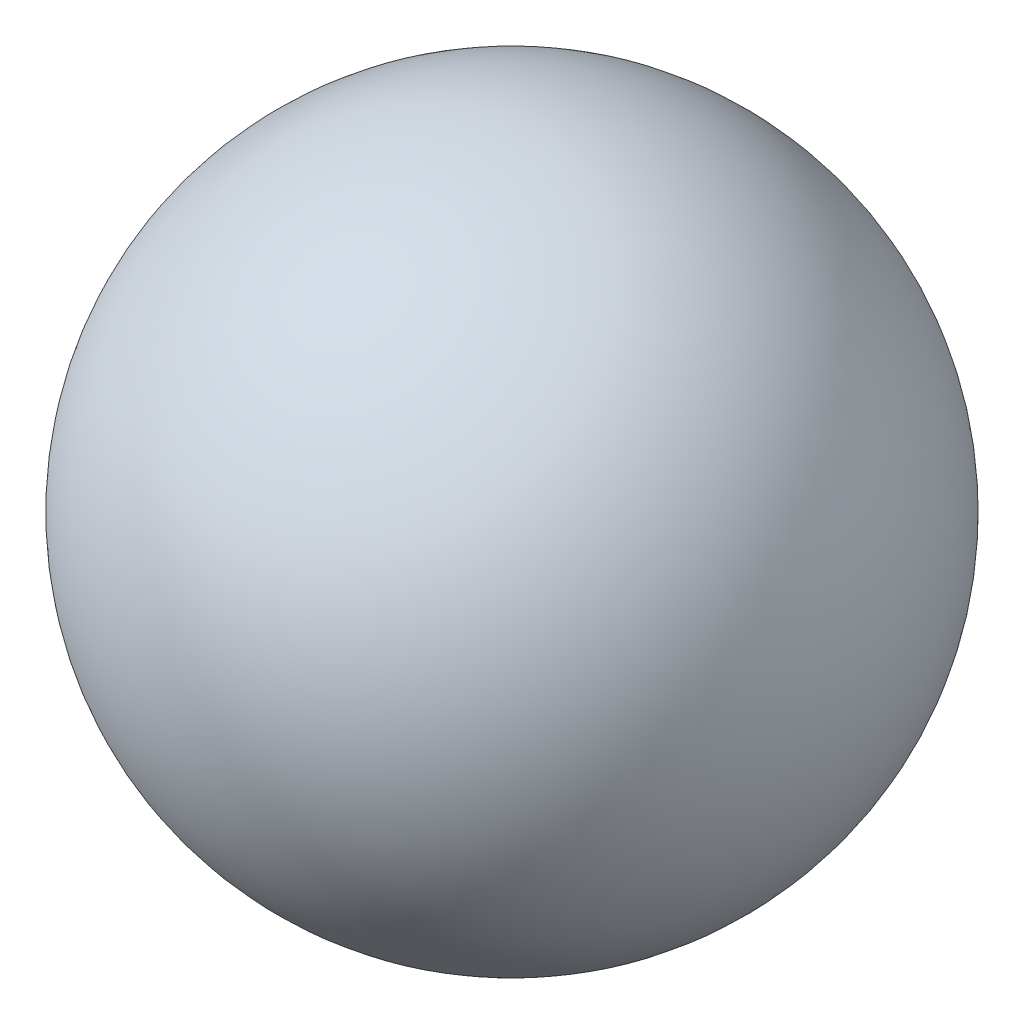
SolidWorks part; units mm, degrees
ref_plane "Front Plane" through (0, 0, 0) normal (0, 0, 1) x (1, 0, 0)
ref_plane "Top Plane" through (0, 0, 0) normal (0, 1, 0) x (1, 0, 0)
ref_plane "Right Plane" through (0, 0, 0) normal (1, 0, 0) x (0, 0, -1)
sketch "Sketch4" plane through (0, 0, 0) normal (1, 0, 0) x (0, 0, -1)
  line L0 (0, 13.9437) -> (0, -13.9437)
  arc A0 (0, -13.9437) -> (0, 13.9437) centre (0, 0) ccw
revolve "Revolve2" add sketch "Sketch4" angle 360 about L0
